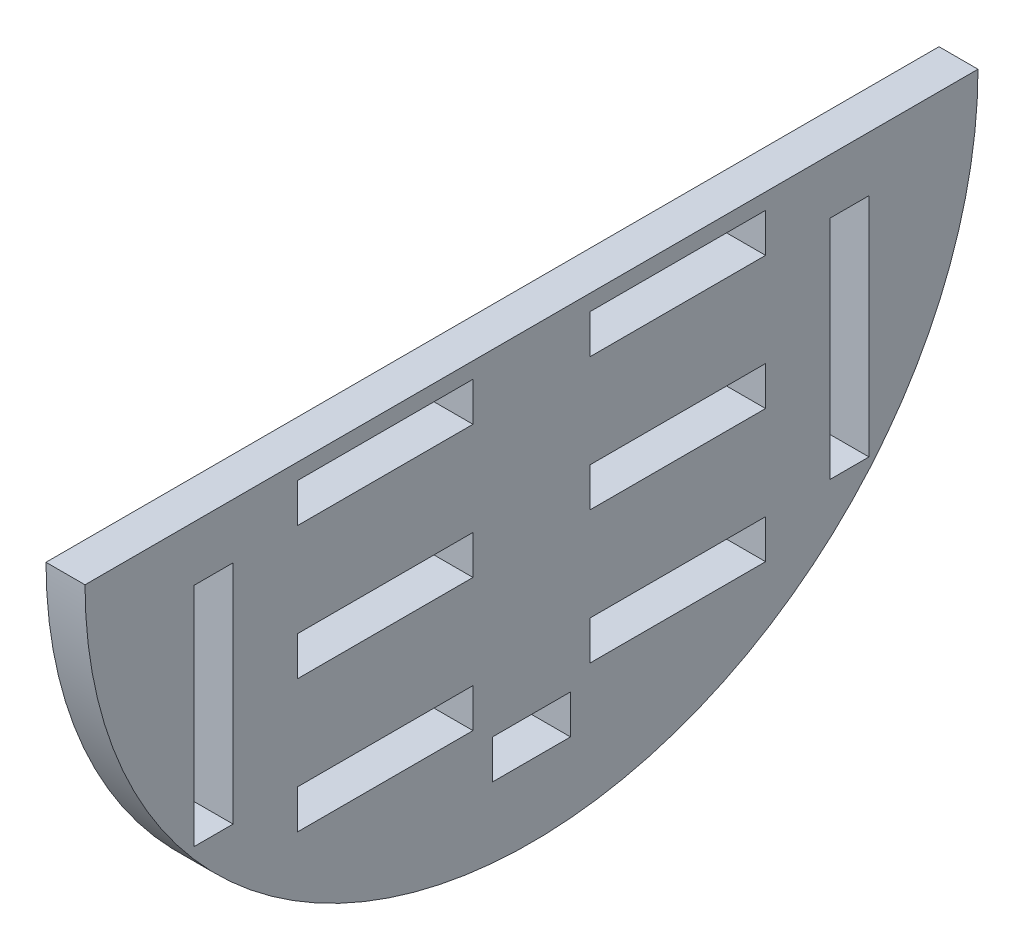
SolidWorks part; units mm, degrees
material "Perspex (TM) GS Acrylic Cast Sheet"
ref_plane "Front Plane" through (0, 0, 0) normal (0, 0, 1) x (1, 0, 0)
ref_plane "Top Plane" through (0, 0, 0) normal (0, 1, 0) x (1, 0, 0)
ref_plane "Right Plane" through (0, 0, 0) normal (1, 0, 0) x (0, 0, -1)
sketch "Sketch1" plane through (0, 0, 0) normal (1, 0, 0) x (0, 0, -1)
  line L0 (0, 0) -> (57.2248, 0)
  line L1 (0, 0) -> (-57.2248, 0)
  line L2 (-38.25, -7.0488) -> (-7.5, -7.0488)
  line L3 (38.25, -7.0488) -> (38.25, -19.0488)
  line L4 (38.25, -19.0488) -> (7.5, -19.0488)
  line L5 (-38.25, -19.0488) -> (-38.25, -7.0488)
  line L6 (-7.5, -2.0488) -> (-7.5, -7.0488)
  line L7 (-5, -48) -> (5, -48)
  line L8 (-5, -48) -> (-5, -43)
  line L9 (-5, -43) -> (5, -43)
  line L10 (5, -48) -> (5, -43)
  line L11 (-5, -48) -> (5, -43) construction
  line L12 (-5, -43) -> (5, -48) construction
  line L17 (-38.25, -24.0488) -> (-7.5, -24.0488)
  line L18 (-38.25, -24.0488) -> (-38.25, -36.0488)
  line L19 (-38.25, -36.0488) -> (-7.5, -36.0488)
  line L20 (38.25, -24.0488) -> (38.25, -36.0488)
  line L45 (30, -19.0488) -> (7.5, -19.0488)
  line L46 (30, -19.0488) -> (30, -24.0488)
  line L47 (30, -24.0488) -> (7.5, -24.0488)
  line L48 (-30, -19.0488) -> (-30, -24.0488)
  line L49 (38.25, -7.0488) -> (43.25, -7.0488)
  line L50 (38.25, -7.0488) -> (38.25, -36.0488)
  line L51 (38.25, -36.0488) -> (43.25, -36.0488)
  line L52 (43.25, -7.0488) -> (43.25, -36.0488)
  line L53 (-38.25, -7.0488) -> (-43.25, -7.0488)
  line L54 (-38.25, -7.0488) -> (-38.25, -36.0488)
  line L55 (-38.25, -36.0488) -> (-43.25, -36.0488)
  line L56 (-43.25, -7.0488) -> (-43.25, -36.0488)
  line L57 (30, -36.0488) -> (7.5, -36.0488)
  line L58 (30, -36.0488) -> (30, -41.0488)
  line L59 (30, -41.0488) -> (7.5, -41.0488)
  line L60 (-30, -36.0488) -> (-30, -41.0488)
  line L61 (30, -7.0488) -> (7.5, -7.0488)
  line L62 (30, -7.0488) -> (30, -2.0488)
  line L63 (30, -2.0488) -> (7.5, -2.0488)
  line L64 (-30, -7.0488) -> (-30, -2.0488)
  line L65 (7.5, -2.0488) -> (7.5, -7.0488)
  line L66 (-7.5, -19.0488) -> (-7.5, -24.0488)
  line L67 (7.5, -19.0488) -> (7.5, -24.0488)
  line L68 (-7.5, -36.0488) -> (-7.5, -41.0488)
  line L69 (7.5, -36.0488) -> (7.5, -41.0488)
  line L70 (7.5, -7.0488) -> (38.25, -7.0488)
  line L71 (-7.5, -7.0488) -> (-30, -7.0488)
  line L72 (-7.5, -2.0488) -> (-30, -2.0488)
  line L73 (-7.5, -19.0488) -> (-38.25, -19.0488)
  line L74 (-7.5, -19.0488) -> (-30, -19.0488)
  line L75 (7.5, -24.0488) -> (38.25, -24.0488)
  line L76 (-7.5, -24.0488) -> (-30, -24.0488)
  line L77 (7.5, -36.0488) -> (38.25, -36.0488)
  line L78 (-7.5, -36.0488) -> (-30, -36.0488)
  line L79 (-7.5, -41.0488) -> (-30, -41.0488)
  arc A0 (-57.2248, 0) -> (57.2248, 0) centre (0, 0) ccw
  point P6 (0, -45.5)
  point P10 (0, -43)
  dimension "D1" = 76.5
  dimension "D2" = 12
  dimension "D3" = 5
  dimension "D4" = 12
  dimension "D5" = 43
  dimension "D6" = 10
  dimension "D7" = 5
  dimension "D8" = 5
  dimension "D9" = 29
  dimension "D10" = 29
  dimension "D11" = 5
  dimension "D12" = 60
  dimension "D13" = 8.25
  dimension "D14" = 8.25
  dimension "D15" = 8.25
  dimension "D16" = 8.25
  dimension "D17" = 5
  dimension "D18" = 5
  dimension "D19" = 60
  dimension "D20" = 8.25
  dimension "D21" = 8.25
  dimension "D22" = 15
  dimension "D23" = 15
  dimension "D24" = 15
  dimension "D25" = 22.5
  dimension "D26" = 5
extrude "Boss-Extrude1" add sketch "Sketch1" along normal blind 5 contours L1 A0 L0 L2 L64 L63 L62 L49 L52 L51 L19 L58 L59 L60 L55 L56 L53 L10 L7 L8 L9 | L5 L4 L3 L2 | L20 L17 L18 L19 | L50 L4 L46 L17 | L4 L54 L17 L48
